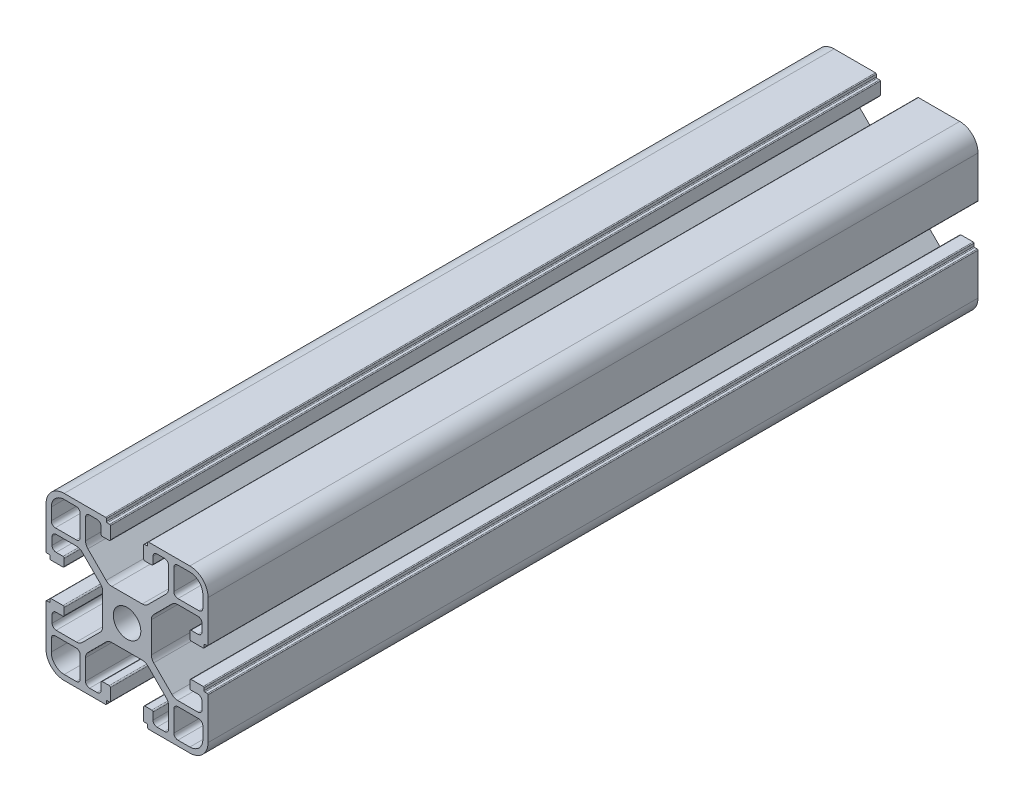
SolidWorks part; units mm, degrees
material "6063-T5"
ref_plane "Front Plane" through (0, 0, 0) normal (0, 0, 1) x (1, 0, 0)
ref_plane "Top Plane" through (0, 0, 0) normal (0, 1, 0) x (1, 0, 0)
ref_plane "Right Plane" through (0, 0, 0) normal (1, 0, 0) x (0, 0, -1)
sketch "Sketch2" plane through (0, 0, 0) normal (0, 0, 1) x (1, 0, 0)
  line L0 (4.5, 0) -> (14.7, 0)
  line L1 (40, 4.5) -> (40, 14.7)
  line L2 (35.5, 40) -> (25.3, 40)
  line L3 (0, 35.5) -> (0, 25.3)
  line L4 (15.9, 1.2) -> (15.9, 4.2)
  line L5 (24.1, 1.2) -> (24.1, 4.2)
  line L6 (38.8, 24.1) -> (35.8, 24.1)
  line L7 (35.5, 24.4) -> (35.5, 26.1)
  line L8 (14, 23.7574) -> (14, 16.2426)
  line L9 (16.2426, 14) -> (23.7574, 14)
  line L10 (26, 16.2426) -> (26, 23.7574)
  line L11 (13.4142, 14.8284) -> (8.9216, 10.3358)
  line L12 (23.7574, 26) -> (16.2426, 26)
  line L13 (4.5, 24.4) -> (4.5, 26.1)
  line L14 (1.2, 24.1) -> (4.2, 24.1)
  line L15 (15.9, 38.8) -> (15.9, 35.8)
  line L16 (14.8284, 26.5858) -> (10.3358, 31.0784)
  line L17 (13.4142, 25.1716) -> (8.9216, 29.6642)
  line L18 (14.8284, 13.4142) -> (10.3358, 8.9216)
  line L19 (25.1716, 13.4142) -> (29.6642, 8.9216)
  line L20 (26.5858, 14.8284) -> (31.0784, 10.3358)
  line L21 (26.5858, 25.1716) -> (31.0784, 29.6642)
  line L22 (25.1716, 26.5858) -> (29.6642, 31.0784)
  line L23 (24.1, 38.8) -> (24.1, 35.8)
  line L24 (14.7, 40) -> (4.5, 40)
  line L25 (25.3, 0) -> (35.5, 0)
  line L26 (38.8, 15.9) -> (35.8, 15.9)
  line L27 (40, 25.3) -> (40, 35.5)
  line L28 (1.2, 15.9) -> (4.2, 15.9)
  line L29 (0, 14.7) -> (0, 4.5)
  line L30 (4.5, 15.6) -> (4.5, 13.9)
  line L31 (35.5, 15.6) -> (35.5, 13.9)
  line L32 (15.6, 35.5) -> (13.9, 35.5)
  line L33 (24.4, 35.5) -> (26.1, 35.5)
  line L34 (15.6, 4.5) -> (13.9, 4.5)
  line L35 (24.4, 4.5) -> (26.1, 4.5)
  line L36 (12.6, 38.5) -> (10.75, 38.5)
  line L37 (1.5, 12.6) -> (1.5, 10.75)
  line L38 (27.4, 1.5) -> (29.25, 1.5)
  line L39 (38.5, 27.4) -> (38.5, 29.25)
  line L40 (38.5, 10.75) -> (38.5, 12.6)
  line L41 (29.25, 38.5) -> (27.4, 38.5)
  line L42 (1.5, 29.25) -> (1.5, 27.4)
  line L43 (10.75, 1.5) -> (12.6, 1.5)
  line L44 (35.8, 26.4) -> (37.5, 26.4)
  line L45 (35.8, 13.6) -> (37.5, 13.6)
  line L46 (4.2, 26.4) -> (2.5, 26.4)
  line L47 (13.6, 35.8) -> (13.6, 37.5)
  line L48 (26.4, 35.8) -> (26.4, 37.5)
  line L49 (4.2, 13.6) -> (2.5, 13.6)
  line L50 (13.6, 4.2) -> (13.6, 2.5)
  line L51 (26.4, 4.2) -> (26.4, 2.5)
  line L52 (9.75, 7.5074) -> (9.75, 2.5)
  line L53 (30.25, 7.5074) -> (30.25, 2.5)
  line L54 (9.75, 37.5) -> (9.75, 32.4926)
  line L55 (30.25, 37.5) -> (30.25, 32.4926)
  line L56 (32.4926, 30.25) -> (37.5, 30.25)
  line L57 (37.5, 9.75) -> (32.4926, 9.75)
  line L58 (2.5, 30.25) -> (7.5074, 30.25)
  line L59 (2.5, 9.75) -> (7.5074, 9.75)
  line L60 (31.55, 37.7) -> (31.55, 32.55)
  line L61 (32.55, 31.55) -> (37.7, 31.55)
  line L62 (1.3, 35.5) -> (1.3, 32.55)
  line L63 (4.5, 38.7) -> (7.45, 38.7)
  line L64 (32.55, 38.7) -> (35.5, 38.7)
  line L65 (38.7, 35.5) -> (38.7, 32.55)
  line L66 (8.45, 37.7) -> (8.45, 32.55)
  line L67 (2.3, 31.55) -> (7.45, 31.55)
  line L68 (1.3, 7.45) -> (1.3, 4.5)
  line L69 (2.3, 8.45) -> (7.45, 8.45)
  line L70 (8.45, 7.45) -> (8.45, 2.3)
  line L71 (4.5, 1.3) -> (7.45, 1.3)
  line L72 (31.55, 7.45) -> (31.55, 2.3)
  line L73 (32.55, 8.45) -> (37.7, 8.45)
  line L74 (38.7, 7.45) -> (38.7, 4.5)
  line L75 (32.55, 1.3) -> (35.5, 1.3)
  line L77 (14.9, 39.8) -> (14.9, 39.2)
  line L78 (15.1, 39) -> (15.7, 39)
  line L79 (25.1, 39.8) -> (25.1, 39.2)
  line L80 (24.9, 39) -> (24.3, 39)
  line L81 (25.1, 0.2) -> (25.1, 0.8)
  line L82 (24.9, 1) -> (24.3, 1)
  line L83 (14.9, 0.2) -> (14.9, 0.8)
  line L84 (15.1, 1) -> (15.7, 1)
  line L85 (0.2, 25.1) -> (0.8, 25.1)
  line L86 (1, 24.9) -> (1, 24.3)
  line L87 (0.2, 14.9) -> (0.8, 14.9)
  line L88 (1, 15.1) -> (1, 15.7)
  line L89 (39.8, 25.1) -> (39.2, 25.1)
  line L90 (39, 24.9) -> (39, 24.3)
  line L91 (39, 15.7) -> (39, 15.1)
  line L92 (39.2, 14.9) -> (39.8, 14.9)
  circle A0 centre (20, 20) radius 3.4
  arc A1 (1.3, 35.5) -> (4.5, 38.7) centre (4.5, 35.5) cw
  arc A2 (1.3, 4.5) -> (4.5, 1.3) centre (4.5, 4.5) ccw
  arc A3 (38.7, 4.5) -> (35.5, 1.3) centre (35.5, 4.5) cw
  arc A4 (35.5, 38.7) -> (38.7, 35.5) centre (35.5, 35.5) cw
  arc A5 (40, 35.5) -> (35.5, 40) centre (35.5, 35.5) ccw
  arc A6 (35.5, 0) -> (40, 4.5) centre (35.5, 4.5) ccw
  arc A7 (4.5, 0) -> (0, 4.5) centre (4.5, 4.5) cw
  arc A8 (4.5, 40) -> (0, 35.5) centre (4.5, 35.5) ccw
  arc A9 (13.4142, 14.8284) -> (14, 16.2426) centre (12, 16.2426) ccw
  arc A10 (7.5074, 9.75) -> (8.9216, 10.3358) centre (7.5074, 11.75) ccw
  arc A11 (9.75, 7.5074) -> (10.3358, 8.9216) centre (11.75, 7.5074) cw
  arc A12 (30.25, 7.5074) -> (29.6642, 8.9216) centre (28.25, 7.5074) ccw
  arc A13 (14.8284, 13.4142) -> (16.2426, 14) centre (16.2426, 12) cw
  arc A14 (25.1716, 13.4142) -> (23.7574, 14) centre (23.7574, 12) ccw
  arc A15 (32.4926, 9.75) -> (31.0784, 10.3358) centre (32.4926, 11.75) cw
  arc A16 (26.5858, 14.8284) -> (26, 16.2426) centre (28, 16.2426) cw
  arc A17 (32.4926, 30.25) -> (31.0784, 29.6642) centre (32.4926, 28.25) ccw
  arc A18 (26.5858, 25.1716) -> (26, 23.7574) centre (28, 23.7574) ccw
  arc A19 (13.4142, 25.1716) -> (14, 23.7574) centre (12, 23.7574) cw
  arc A20 (7.5074, 30.25) -> (8.9216, 29.6642) centre (7.5074, 28.25) cw
  arc A21 (9.75, 32.4926) -> (10.3358, 31.0784) centre (11.75, 32.4926) ccw
  arc A22 (30.25, 32.4926) -> (29.6642, 31.0784) centre (28.25, 32.4926) cw
  arc A23 (25.1716, 26.5858) -> (23.7574, 26) centre (23.7574, 28) cw
  arc A24 (14.8284, 26.5858) -> (16.2426, 26) centre (16.2426, 28) ccw
  arc A25 (37.7, 8.45) -> (38.7, 7.45) centre (37.7, 7.45) cw
  arc A26 (31.55, 2.3) -> (32.55, 1.3) centre (32.55, 2.3) ccw
  arc A27 (31.55, 7.45) -> (32.55, 8.45) centre (32.55, 7.45) cw
  arc A28 (8.45, 2.3) -> (7.45, 1.3) centre (7.45, 2.3) cw
  arc A29 (1.3, 7.45) -> (2.3, 8.45) centre (2.3, 7.45) cw
  arc A30 (7.45, 8.45) -> (8.45, 7.45) centre (7.45, 7.45) cw
  arc A31 (38.7, 32.55) -> (37.7, 31.55) centre (37.7, 32.55) cw
  arc A32 (31.55, 32.55) -> (32.55, 31.55) centre (32.55, 32.55) ccw
  arc A33 (31.55, 37.7) -> (32.55, 38.7) centre (32.55, 37.7) cw
  arc A34 (7.45, 38.7) -> (8.45, 37.7) centre (7.45, 37.7) cw
  arc A35 (8.45, 32.55) -> (7.45, 31.55) centre (7.45, 32.55) cw
  arc A36 (1.3, 32.55) -> (2.3, 31.55) centre (2.3, 32.55) ccw
  arc A37 (30.25, 2.5) -> (29.25, 1.5) centre (29.25, 2.5) cw
  arc A38 (26.4, 2.5) -> (27.4, 1.5) centre (27.4, 2.5) ccw
  arc A39 (13.6, 2.5) -> (12.6, 1.5) centre (12.6, 2.5) cw
  arc A40 (9.75, 2.5) -> (10.75, 1.5) centre (10.75, 2.5) ccw
  arc A41 (26.4, 37.5) -> (27.4, 38.5) centre (27.4, 37.5) cw
  arc A42 (30.25, 37.5) -> (29.25, 38.5) centre (29.25, 37.5) ccw
  arc A43 (37.5, 26.4) -> (38.5, 27.4) centre (37.5, 27.4) ccw
  arc A44 (37.5, 30.25) -> (38.5, 29.25) centre (37.5, 29.25) cw
  arc A45 (37.5, 13.6) -> (38.5, 12.6) centre (37.5, 12.6) cw
  arc A46 (37.5, 9.75) -> (38.5, 10.75) centre (37.5, 10.75) ccw
  arc A47 (2.5, 9.75) -> (1.5, 10.75) centre (2.5, 10.75) cw
  arc A48 (2.5, 13.6) -> (1.5, 12.6) centre (2.5, 12.6) ccw
  arc A49 (2.5, 26.4) -> (1.5, 27.4) centre (2.5, 27.4) cw
  arc A50 (2.5, 30.25) -> (1.5, 29.25) centre (2.5, 29.25) ccw
  arc A51 (9.75, 37.5) -> (10.75, 38.5) centre (10.75, 37.5) cw
  arc A52 (13.6, 37.5) -> (12.6, 38.5) centre (12.6, 37.5) ccw
  arc A53 (26.1, 35.5) -> (26.4, 35.8) centre (26.1, 35.8) ccw
  arc A54 (24.1, 35.8) -> (24.4, 35.5) centre (24.4, 35.8) ccw
  arc A55 (15.9, 35.8) -> (15.6, 35.5) centre (15.6, 35.8) cw
  arc A56 (13.9, 35.5) -> (13.6, 35.8) centre (13.9, 35.8) cw
  arc A57 (13.9, 4.5) -> (13.6, 4.2) centre (13.9, 4.2) ccw
  arc A58 (15.9, 4.2) -> (15.6, 4.5) centre (15.6, 4.2) ccw
  arc A59 (24.1, 4.2) -> (24.4, 4.5) centre (24.4, 4.2) cw
  arc A60 (26.1, 4.5) -> (26.4, 4.2) centre (26.1, 4.2) cw
  arc A61 (35.5, 13.9) -> (35.8, 13.6) centre (35.8, 13.9) ccw
  arc A62 (35.8, 15.9) -> (35.5, 15.6) centre (35.8, 15.6) ccw
  arc A63 (35.8, 24.1) -> (35.5, 24.4) centre (35.8, 24.4) cw
  arc A64 (35.5, 26.1) -> (35.8, 26.4) centre (35.8, 26.1) cw
  arc A65 (4.5, 13.9) -> (4.2, 13.6) centre (4.2, 13.9) cw
  arc A66 (4.2, 15.9) -> (4.5, 15.6) centre (4.2, 15.6) cw
  arc A67 (4.2, 24.1) -> (4.5, 24.4) centre (4.2, 24.4) ccw
  arc A68 (4.5, 26.1) -> (4.2, 26.4) centre (4.2, 26.1) ccw
  arc A69 (25.3, 0) -> (25.1, 0.2) centre (25.3, 0.2) cw
  arc A70 (25.1, 0.8) -> (24.9, 1) centre (24.9, 0.8) ccw
  arc A71 (24.3, 1) -> (24.1, 1.2) centre (24.3, 1.2) cw
  arc A72 (14.7, 0) -> (14.9, 0.2) centre (14.7, 0.2) ccw
  arc A73 (14.9, 0.8) -> (15.1, 1) centre (15.1, 0.8) cw
  arc A74 (15.7, 1) -> (15.9, 1.2) centre (15.7, 1.2) ccw
  arc A75 (39.8, 14.9) -> (40, 14.7) centre (39.8, 14.7) cw
  arc A76 (39, 15.1) -> (39.2, 14.9) centre (39.2, 15.1) ccw
  arc A77 (38.8, 15.9) -> (39, 15.7) centre (38.8, 15.7) cw
  arc A78 (0, 25.3) -> (0.2, 25.1) centre (0.2, 25.3) ccw
  arc A79 (0.8, 25.1) -> (1, 24.9) centre (0.8, 24.9) cw
  arc A80 (1, 24.3) -> (1.2, 24.1) centre (1.2, 24.3) ccw
  arc A81 (0, 14.7) -> (0.2, 14.9) centre (0.2, 14.7) cw
  arc A82 (0.8, 14.9) -> (1, 15.1) centre (0.8, 15.1) ccw
  arc A83 (1, 15.7) -> (1.2, 15.9) centre (1.2, 15.7) cw
  arc A84 (39, 24.3) -> (38.8, 24.1) centre (38.8, 24.3) cw
  arc A85 (39.2, 25.1) -> (39, 24.9) centre (39.2, 24.9) ccw
  arc A86 (40, 25.3) -> (39.8, 25.1) centre (39.8, 25.3) cw
  arc A87 (24.3, 39) -> (24.1, 38.8) centre (24.3, 38.8) ccw
  arc A88 (25.1, 39.2) -> (24.9, 39) centre (24.9, 39.2) cw
  arc A89 (25.3, 40) -> (25.1, 39.8) centre (25.3, 39.8) ccw
  arc A90 (14.9, 39.2) -> (15.1, 39) centre (15.1, 39.2) ccw
  arc A91 (15.7, 39) -> (15.9, 38.8) centre (15.7, 38.8) cw
  arc A92 (14.7, 40) -> (14.9, 39.8) centre (14.7, 39.8) cw
  point P93 (0, 0)
extrude "Boss-Extrude1" add sketch "Sketch2" along normal blind 190
sketch "Sketch3" plane through (0, 0, 190) normal (0, 0, 1) x (1, 0, 0)
  line L76 (25.3, 0) -> (35.5, 0)
  line L77 (40, 4.5) -> (40, 14.7)
  line L78 (39.8, 14.9) -> (39.2, 14.9)
  line L79 (39, 15.1) -> (39, 15.7)
  line L80 (38.8, 15.9) -> (35.8, 15.9)
  line L81 (35.5, 15.6) -> (35.5, 13.9)
  line L82 (35.8, 13.6) -> (37.5, 13.6)
  line L83 (38.5, 12.6) -> (38.5, 10.75)
  line L84 (37.5, 9.75) -> (32.4926, 9.75)
  line L85 (31.0784, 10.3358) -> (26.5858, 14.8284)
  line L86 (26, 16.2426) -> (26, 23.7574)
  line L87 (26.5858, 25.1716) -> (31.0784, 29.6642)
  line L88 (32.4926, 30.25) -> (37.5, 30.25)
  line L89 (38.5, 29.25) -> (38.5, 27.4)
  line L90 (37.5, 26.4) -> (35.8, 26.4)
  line L91 (35.5, 26.1) -> (35.5, 24.4)
  line L92 (35.8, 24.1) -> (38.8, 24.1)
  line L93 (39, 24.3) -> (39, 24.9)
  line L94 (39.2, 25.1) -> (39.8, 25.1)
  line L95 (40, 25.3) -> (40, 35.5)
  line L96 (35.5, 40) -> (25.3, 40)
  line L97 (25.1, 39.8) -> (25.1, 39.2)
  line L98 (24.9, 39) -> (24.3, 39)
  line L99 (24.1, 38.8) -> (24.1, 35.8)
  line L100 (24.4, 35.5) -> (26.1, 35.5)
  line L101 (26.4, 35.8) -> (26.4, 37.5)
  line L102 (27.4, 38.5) -> (29.25, 38.5)
  line L103 (30.25, 37.5) -> (30.25, 32.4926)
  line L104 (29.6642, 31.0784) -> (25.1716, 26.5858)
  line L105 (23.7574, 26) -> (16.2426, 26)
  line L106 (14.8284, 26.5858) -> (10.3358, 31.0784)
  line L107 (9.75, 32.4926) -> (9.75, 37.5)
  line L108 (10.75, 38.5) -> (12.6, 38.5)
  line L109 (13.6, 37.5) -> (13.6, 35.8)
  line L110 (13.9, 35.5) -> (15.6, 35.5)
  line L111 (15.9, 35.8) -> (15.9, 38.8)
  line L112 (15.7, 39) -> (15.1, 39)
  line L113 (14.9, 39.2) -> (14.9, 39.8)
  line L114 (14.7, 40) -> (4.5, 40)
  line L115 (0, 35.5) -> (0, 25.3)
  line L116 (0.2, 25.1) -> (0.8, 25.1)
  line L117 (1, 24.9) -> (1, 24.3)
  line L118 (1.2, 24.1) -> (4.2, 24.1)
  line L119 (4.5, 24.4) -> (4.5, 26.1)
  line L120 (4.2, 26.4) -> (2.5, 26.4)
  line L121 (1.5, 27.4) -> (1.5, 29.25)
  line L122 (2.5, 30.25) -> (7.5074, 30.25)
  line L123 (8.9216, 29.6642) -> (13.4142, 25.1716)
  line L124 (14, 23.7574) -> (14, 16.2426)
  line L125 (13.4142, 14.8284) -> (8.9216, 10.3358)
  line L126 (7.5074, 9.75) -> (2.5, 9.75)
  line L127 (1.5, 10.75) -> (1.5, 12.6)
  line L128 (2.5, 13.6) -> (4.2, 13.6)
  line L129 (4.5, 13.9) -> (4.5, 15.6)
  line L130 (4.2, 15.9) -> (1.2, 15.9)
  line L131 (1, 15.7) -> (1, 15.1)
  line L132 (0.8, 14.9) -> (0.2, 14.9)
  line L133 (0, 14.7) -> (0, 4.5)
  line L134 (4.5, 0) -> (14.7, 0)
  line L135 (14.9, 0.2) -> (14.9, 0.8)
  line L136 (15.1, 1) -> (15.7, 1)
  line L137 (15.9, 1.2) -> (15.9, 4.2)
  line L138 (15.6, 4.5) -> (13.9, 4.5)
  line L139 (13.6, 4.2) -> (13.6, 2.5)
  line L140 (12.6, 1.5) -> (10.75, 1.5)
  line L141 (9.75, 2.5) -> (9.75, 7.5074)
  line L142 (10.3358, 8.9216) -> (14.8284, 13.4142)
  line L143 (16.2426, 14) -> (23.7574, 14)
  line L144 (25.1716, 13.4142) -> (29.6642, 8.9216)
  line L145 (30.25, 7.5074) -> (30.25, 2.5)
  line L146 (29.25, 1.5) -> (27.4, 1.5)
  line L147 (26.4, 2.5) -> (26.4, 4.2)
  line L148 (26.1, 4.5) -> (24.4, 4.5)
  line L149 (24.1, 4.2) -> (24.1, 1.2)
  line L150 (24.3, 1) -> (24.9, 1)
  line L151 (25.1, 0.8) -> (25.1, 0.2)
  line L152 (25.3, 0) -> (35.5, 0)
  line L153 (40, 4.5) -> (40, 14.7)
  line L154 (39.8, 14.9) -> (39.2, 14.9)
  line L155 (39, 15.1) -> (39, 15.7)
  line L156 (38.8, 15.9) -> (35.8, 15.9)
  line L157 (35.5, 15.6) -> (35.5, 13.9)
  line L158 (35.8, 13.6) -> (37.5, 13.6)
  line L159 (38.5, 12.6) -> (38.5, 10.75)
  line L160 (37.5, 9.75) -> (32.4926, 9.75)
  line L161 (31.0784, 10.3358) -> (26.5858, 14.8284)
  line L162 (26, 16.2426) -> (26, 23.7574)
  line L163 (26.5858, 25.1716) -> (31.0784, 29.6642)
  line L164 (32.4926, 30.25) -> (37.5, 30.25)
  line L165 (38.5, 29.25) -> (38.5, 27.4)
  line L166 (37.5, 26.4) -> (35.8, 26.4)
  line L167 (35.5, 26.1) -> (35.5, 24.4)
  line L168 (35.8, 24.1) -> (38.8, 24.1)
  line L169 (39, 24.3) -> (39, 24.9)
  line L170 (39.2, 25.1) -> (39.8, 25.1)
  line L171 (40, 25.3) -> (40, 35.5)
  line L172 (35.5, 40) -> (25.3, 40)
  line L173 (25.1, 39.8) -> (25.1, 39.2)
  line L174 (24.9, 39) -> (24.3, 39)
  line L175 (24.1, 38.8) -> (24.1, 35.8)
  line L176 (24.4, 35.5) -> (26.1, 35.5)
  line L177 (26.4, 35.8) -> (26.4, 37.5)
  line L178 (27.4, 38.5) -> (29.25, 38.5)
  line L179 (30.25, 37.5) -> (30.25, 32.4926)
  line L180 (29.6642, 31.0784) -> (25.1716, 26.5858)
  line L181 (23.7574, 26) -> (16.2426, 26)
  line L182 (14.8284, 26.5858) -> (10.3358, 31.0784)
  line L183 (9.75, 32.4926) -> (9.75, 37.5)
  line L184 (10.75, 38.5) -> (12.6, 38.5)
  line L185 (13.6, 37.5) -> (13.6, 35.8)
  line L186 (13.9, 35.5) -> (15.6, 35.5)
  line L187 (15.9, 35.8) -> (15.9, 38.8)
  line L188 (15.7, 39) -> (15.1, 39)
  line L189 (14.9, 39.2) -> (14.9, 39.8)
  line L190 (14.7, 40) -> (4.5, 40)
  line L191 (0, 35.5) -> (0, 25.3)
  line L192 (0.2, 25.1) -> (0.8, 25.1)
  line L193 (1, 24.9) -> (1, 24.3)
  line L194 (1.2, 24.1) -> (4.2, 24.1)
  line L195 (4.5, 24.4) -> (4.5, 26.1)
  line L196 (4.2, 26.4) -> (2.5, 26.4)
  line L197 (1.5, 27.4) -> (1.5, 29.25)
  line L198 (2.5, 30.25) -> (7.5074, 30.25)
  line L199 (8.9216, 29.6642) -> (13.4142, 25.1716)
  line L200 (14, 23.7574) -> (14, 16.2426)
  line L201 (13.4142, 14.8284) -> (8.9216, 10.3358)
  line L202 (7.5074, 9.75) -> (2.5, 9.75)
  line L203 (1.5, 10.75) -> (1.5, 12.6)
  line L204 (2.5, 13.6) -> (4.2, 13.6)
  line L205 (4.5, 13.9) -> (4.5, 15.6)
  line L206 (4.2, 15.9) -> (1.2, 15.9)
  line L207 (1, 15.7) -> (1, 15.1)
  line L208 (0.8, 14.9) -> (0.2, 14.9)
  line L209 (0, 14.7) -> (0, 4.5)
  line L210 (4.5, 0) -> (14.7, 0)
  line L211 (14.9, 0.2) -> (14.9, 0.8)
  line L212 (15.1, 1) -> (15.7, 1)
  line L213 (15.9, 1.2) -> (15.9, 4.2)
  line L214 (15.6, 4.5) -> (13.9, 4.5)
  line L215 (13.6, 4.2) -> (13.6, 2.5)
  line L216 (12.6, 1.5) -> (10.75, 1.5)
  line L217 (9.75, 2.5) -> (9.75, 7.5074)
  line L218 (10.3358, 8.9216) -> (14.8284, 13.4142)
  line L219 (16.2426, 14) -> (23.7574, 14)
  line L220 (25.1716, 13.4142) -> (29.6642, 8.9216)
  line L221 (30.25, 7.5074) -> (30.25, 2.5)
  line L222 (29.25, 1.5) -> (27.4, 1.5)
  line L223 (26.4, 2.5) -> (26.4, 4.2)
  line L224 (26.1, 4.5) -> (24.4, 4.5)
  line L225 (24.1, 4.2) -> (24.1, 1.2)
  line L226 (24.3, 1) -> (24.9, 1)
  line L227 (25.1, 0.8) -> (25.1, 0.2)
  arc A76 (25.1, 0.2) -> (25.3, 0) centre (25.3, 0.2) ccw
  arc A77 (35.5, 0) -> (40, 4.5) centre (35.5, 4.5) ccw
  arc A78 (40, 14.7) -> (39.8, 14.9) centre (39.8, 14.7) ccw
  arc A79 (39, 15.1) -> (39.2, 14.9) centre (39.2, 15.1) ccw
  arc A80 (39, 15.7) -> (38.8, 15.9) centre (38.8, 15.7) ccw
  arc A81 (35.8, 15.9) -> (35.5, 15.6) centre (35.8, 15.6) ccw
  arc A82 (35.5, 13.9) -> (35.8, 13.6) centre (35.8, 13.9) ccw
  arc A83 (38.5, 12.6) -> (37.5, 13.6) centre (37.5, 12.6) ccw
  arc A84 (37.5, 9.75) -> (38.5, 10.75) centre (37.5, 10.75) ccw
  arc A85 (31.0784, 10.3358) -> (32.4926, 9.75) centre (32.4926, 11.75) ccw
  arc A86 (26, 16.2426) -> (26.5858, 14.8284) centre (28, 16.2426) ccw
  arc A87 (26.5858, 25.1716) -> (26, 23.7574) centre (28, 23.7574) ccw
  arc A88 (32.4926, 30.25) -> (31.0784, 29.6642) centre (32.4926, 28.25) ccw
  arc A89 (38.5, 29.25) -> (37.5, 30.25) centre (37.5, 29.25) ccw
  arc A90 (37.5, 26.4) -> (38.5, 27.4) centre (37.5, 27.4) ccw
  arc A91 (35.8, 26.4) -> (35.5, 26.1) centre (35.8, 26.1) ccw
  arc A92 (35.5, 24.4) -> (35.8, 24.1) centre (35.8, 24.4) ccw
  arc A93 (38.8, 24.1) -> (39, 24.3) centre (38.8, 24.3) ccw
  arc A94 (39.2, 25.1) -> (39, 24.9) centre (39.2, 24.9) ccw
  arc A95 (39.8, 25.1) -> (40, 25.3) centre (39.8, 25.3) ccw
  arc A96 (40, 35.5) -> (35.5, 40) centre (35.5, 35.5) ccw
  arc A97 (25.3, 40) -> (25.1, 39.8) centre (25.3, 39.8) ccw
  arc A98 (24.9, 39) -> (25.1, 39.2) centre (24.9, 39.2) ccw
  arc A99 (24.3, 39) -> (24.1, 38.8) centre (24.3, 38.8) ccw
  arc A100 (24.1, 35.8) -> (24.4, 35.5) centre (24.4, 35.8) ccw
  arc A101 (26.1, 35.5) -> (26.4, 35.8) centre (26.1, 35.8) ccw
  arc A102 (27.4, 38.5) -> (26.4, 37.5) centre (27.4, 37.5) ccw
  arc A103 (30.25, 37.5) -> (29.25, 38.5) centre (29.25, 37.5) ccw
  arc A104 (29.6642, 31.0784) -> (30.25, 32.4926) centre (28.25, 32.4926) ccw
  arc A105 (23.7574, 26) -> (25.1716, 26.5858) centre (23.7574, 28) ccw
  arc A106 (14.8284, 26.5858) -> (16.2426, 26) centre (16.2426, 28) ccw
  arc A107 (9.75, 32.4926) -> (10.3358, 31.0784) centre (11.75, 32.4926) ccw
  arc A108 (10.75, 38.5) -> (9.75, 37.5) centre (10.75, 37.5) ccw
  arc A109 (13.6, 37.5) -> (12.6, 38.5) centre (12.6, 37.5) ccw
  arc A110 (13.6, 35.8) -> (13.9, 35.5) centre (13.9, 35.8) ccw
  arc A111 (15.6, 35.5) -> (15.9, 35.8) centre (15.6, 35.8) ccw
  arc A112 (15.9, 38.8) -> (15.7, 39) centre (15.7, 38.8) ccw
  arc A113 (14.9, 39.2) -> (15.1, 39) centre (15.1, 39.2) ccw
  arc A114 (14.9, 39.8) -> (14.7, 40) centre (14.7, 39.8) ccw
  arc A115 (4.5, 40) -> (0, 35.5) centre (4.5, 35.5) ccw
  arc A116 (0, 25.3) -> (0.2, 25.1) centre (0.2, 25.3) ccw
  arc A117 (1, 24.9) -> (0.8, 25.1) centre (0.8, 24.9) ccw
  arc A118 (1, 24.3) -> (1.2, 24.1) centre (1.2, 24.3) ccw
  arc A119 (4.2, 24.1) -> (4.5, 24.4) centre (4.2, 24.4) ccw
  arc A120 (4.5, 26.1) -> (4.2, 26.4) centre (4.2, 26.1) ccw
  arc A121 (1.5, 27.4) -> (2.5, 26.4) centre (2.5, 27.4) ccw
  arc A122 (2.5, 30.25) -> (1.5, 29.25) centre (2.5, 29.25) ccw
  arc A123 (8.9216, 29.6642) -> (7.5074, 30.25) centre (7.5074, 28.25) ccw
  arc A124 (14, 23.7574) -> (13.4142, 25.1716) centre (12, 23.7574) ccw
  arc A125 (13.4142, 14.8284) -> (14, 16.2426) centre (12, 16.2426) ccw
  arc A126 (7.5074, 9.75) -> (8.9216, 10.3358) centre (7.5074, 11.75) ccw
  arc A127 (1.5, 10.75) -> (2.5, 9.75) centre (2.5, 10.75) ccw
  arc A128 (2.5, 13.6) -> (1.5, 12.6) centre (2.5, 12.6) ccw
  arc A129 (4.2, 13.6) -> (4.5, 13.9) centre (4.2, 13.9) ccw
  arc A130 (4.5, 15.6) -> (4.2, 15.9) centre (4.2, 15.6) ccw
  arc A131 (1.2, 15.9) -> (1, 15.7) centre (1.2, 15.7) ccw
  arc A132 (0.8, 14.9) -> (1, 15.1) centre (0.8, 15.1) ccw
  arc A133 (0.2, 14.9) -> (0, 14.7) centre (0.2, 14.7) ccw
  arc A134 (0, 4.5) -> (4.5, 0) centre (4.5, 4.5) ccw
  arc A135 (14.7, 0) -> (14.9, 0.2) centre (14.7, 0.2) ccw
  arc A136 (15.1, 1) -> (14.9, 0.8) centre (15.1, 0.8) ccw
  arc A137 (15.7, 1) -> (15.9, 1.2) centre (15.7, 1.2) ccw
  arc A138 (15.9, 4.2) -> (15.6, 4.5) centre (15.6, 4.2) ccw
  arc A139 (13.9, 4.5) -> (13.6, 4.2) centre (13.9, 4.2) ccw
  arc A140 (12.6, 1.5) -> (13.6, 2.5) centre (12.6, 2.5) ccw
  arc A141 (9.75, 2.5) -> (10.75, 1.5) centre (10.75, 2.5) ccw
  arc A142 (10.3358, 8.9216) -> (9.75, 7.5074) centre (11.75, 7.5074) ccw
  arc A143 (16.2426, 14) -> (14.8284, 13.4142) centre (16.2426, 12) ccw
  arc A144 (25.1716, 13.4142) -> (23.7574, 14) centre (23.7574, 12) ccw
  arc A145 (30.25, 7.5074) -> (29.6642, 8.9216) centre (28.25, 7.5074) ccw
  arc A146 (29.25, 1.5) -> (30.25, 2.5) centre (29.25, 2.5) ccw
  arc A147 (26.4, 2.5) -> (27.4, 1.5) centre (27.4, 2.5) ccw
  arc A148 (26.4, 4.2) -> (26.1, 4.5) centre (26.1, 4.2) ccw
  arc A149 (24.4, 4.5) -> (24.1, 4.2) centre (24.4, 4.2) ccw
  arc A150 (24.1, 1.2) -> (24.3, 1) centre (24.3, 1.2) ccw
  arc A151 (25.1, 0.8) -> (24.9, 1) centre (24.9, 0.8) ccw
  arc A152 (25.1, 0.2) -> (25.3, 0) centre (25.3, 0.2) ccw
  arc A153 (35.5, 0) -> (40, 4.5) centre (35.5, 4.5) ccw
  arc A154 (40, 14.7) -> (39.8, 14.9) centre (39.8, 14.7) ccw
  arc A155 (39, 15.1) -> (39.2, 14.9) centre (39.2, 15.1) ccw
  arc A156 (39, 15.7) -> (38.8, 15.9) centre (38.8, 15.7) ccw
  arc A157 (35.8, 15.9) -> (35.5, 15.6) centre (35.8, 15.6) ccw
  arc A158 (35.5, 13.9) -> (35.8, 13.6) centre (35.8, 13.9) ccw
  arc A159 (38.5, 12.6) -> (37.5, 13.6) centre (37.5, 12.6) ccw
  arc A160 (37.5, 9.75) -> (38.5, 10.75) centre (37.5, 10.75) ccw
  arc A161 (31.0784, 10.3358) -> (32.4926, 9.75) centre (32.4926, 11.75) ccw
  arc A162 (26, 16.2426) -> (26.5858, 14.8284) centre (28, 16.2426) ccw
  arc A163 (26.5858, 25.1716) -> (26, 23.7574) centre (28, 23.7574) ccw
  arc A164 (32.4926, 30.25) -> (31.0784, 29.6642) centre (32.4926, 28.25) ccw
  arc A165 (38.5, 29.25) -> (37.5, 30.25) centre (37.5, 29.25) ccw
  arc A166 (37.5, 26.4) -> (38.5, 27.4) centre (37.5, 27.4) ccw
  arc A167 (35.8, 26.4) -> (35.5, 26.1) centre (35.8, 26.1) ccw
  arc A168 (35.5, 24.4) -> (35.8, 24.1) centre (35.8, 24.4) ccw
  arc A169 (38.8, 24.1) -> (39, 24.3) centre (38.8, 24.3) ccw
  arc A170 (39.2, 25.1) -> (39, 24.9) centre (39.2, 24.9) ccw
  arc A171 (39.8, 25.1) -> (40, 25.3) centre (39.8, 25.3) ccw
  arc A172 (40, 35.5) -> (35.5, 40) centre (35.5, 35.5) ccw
  arc A173 (25.3, 40) -> (25.1, 39.8) centre (25.3, 39.8) ccw
  arc A174 (24.9, 39) -> (25.1, 39.2) centre (24.9, 39.2) ccw
  arc A175 (24.3, 39) -> (24.1, 38.8) centre (24.3, 38.8) ccw
  arc A176 (24.1, 35.8) -> (24.4, 35.5) centre (24.4, 35.8) ccw
  arc A177 (26.1, 35.5) -> (26.4, 35.8) centre (26.1, 35.8) ccw
  arc A178 (27.4, 38.5) -> (26.4, 37.5) centre (27.4, 37.5) ccw
  arc A179 (30.25, 37.5) -> (29.25, 38.5) centre (29.25, 37.5) ccw
  arc A180 (29.6642, 31.0784) -> (30.25, 32.4926) centre (28.25, 32.4926) ccw
  arc A181 (23.7574, 26) -> (25.1716, 26.5858) centre (23.7574, 28) ccw
  arc A182 (14.8284, 26.5858) -> (16.2426, 26) centre (16.2426, 28) ccw
  arc A183 (9.75, 32.4926) -> (10.3358, 31.0784) centre (11.75, 32.4926) ccw
  arc A184 (10.75, 38.5) -> (9.75, 37.5) centre (10.75, 37.5) ccw
  arc A185 (13.6, 37.5) -> (12.6, 38.5) centre (12.6, 37.5) ccw
  arc A186 (13.6, 35.8) -> (13.9, 35.5) centre (13.9, 35.8) ccw
  arc A187 (15.6, 35.5) -> (15.9, 35.8) centre (15.6, 35.8) ccw
  arc A188 (15.9, 38.8) -> (15.7, 39) centre (15.7, 38.8) ccw
  arc A189 (14.9, 39.2) -> (15.1, 39) centre (15.1, 39.2) ccw
  arc A190 (14.9, 39.8) -> (14.7, 40) centre (14.7, 39.8) ccw
  arc A191 (4.5, 40) -> (0, 35.5) centre (4.5, 35.5) ccw
  arc A192 (0, 25.3) -> (0.2, 25.1) centre (0.2, 25.3) ccw
  arc A193 (1, 24.9) -> (0.8, 25.1) centre (0.8, 24.9) ccw
  arc A194 (1, 24.3) -> (1.2, 24.1) centre (1.2, 24.3) ccw
  arc A195 (4.2, 24.1) -> (4.5, 24.4) centre (4.2, 24.4) ccw
  arc A196 (4.5, 26.1) -> (4.2, 26.4) centre (4.2, 26.1) ccw
  arc A197 (1.5, 27.4) -> (2.5, 26.4) centre (2.5, 27.4) ccw
  arc A198 (2.5, 30.25) -> (1.5, 29.25) centre (2.5, 29.25) ccw
  arc A199 (8.9216, 29.6642) -> (7.5074, 30.25) centre (7.5074, 28.25) ccw
  arc A200 (14, 23.7574) -> (13.4142, 25.1716) centre (12, 23.7574) ccw
  arc A201 (13.4142, 14.8284) -> (14, 16.2426) centre (12, 16.2426) ccw
  arc A202 (7.5074, 9.75) -> (8.9216, 10.3358) centre (7.5074, 11.75) ccw
  arc A203 (1.5, 10.75) -> (2.5, 9.75) centre (2.5, 10.75) ccw
  arc A204 (2.5, 13.6) -> (1.5, 12.6) centre (2.5, 12.6) ccw
  arc A205 (4.2, 13.6) -> (4.5, 13.9) centre (4.2, 13.9) ccw
  arc A206 (4.5, 15.6) -> (4.2, 15.9) centre (4.2, 15.6) ccw
  arc A207 (1.2, 15.9) -> (1, 15.7) centre (1.2, 15.7) ccw
  arc A208 (0.8, 14.9) -> (1, 15.1) centre (0.8, 15.1) ccw
  arc A209 (0.2, 14.9) -> (0, 14.7) centre (0.2, 14.7) ccw
  arc A210 (0, 4.5) -> (4.5, 0) centre (4.5, 4.5) ccw
  arc A211 (14.7, 0) -> (14.9, 0.2) centre (14.7, 0.2) ccw
  arc A212 (15.1, 1) -> (14.9, 0.8) centre (15.1, 0.8) ccw
  arc A213 (15.7, 1) -> (15.9, 1.2) centre (15.7, 1.2) ccw
  arc A214 (15.9, 4.2) -> (15.6, 4.5) centre (15.6, 4.2) ccw
  arc A215 (13.9, 4.5) -> (13.6, 4.2) centre (13.9, 4.2) ccw
  arc A216 (12.6, 1.5) -> (13.6, 2.5) centre (12.6, 2.5) ccw
  arc A217 (9.75, 2.5) -> (10.75, 1.5) centre (10.75, 2.5) ccw
  arc A218 (10.3358, 8.9216) -> (9.75, 7.5074) centre (11.75, 7.5074) ccw
  arc A219 (16.2426, 14) -> (14.8284, 13.4142) centre (16.2426, 12) ccw
  arc A220 (25.1716, 13.4142) -> (23.7574, 14) centre (23.7574, 12) ccw
  arc A221 (30.25, 7.5074) -> (29.6642, 8.9216) centre (28.25, 7.5074) ccw
  arc A222 (29.25, 1.5) -> (30.25, 2.5) centre (29.25, 2.5) ccw
  arc A223 (26.4, 2.5) -> (27.4, 1.5) centre (27.4, 2.5) ccw
  arc A224 (26.4, 4.2) -> (26.1, 4.5) centre (26.1, 4.2) ccw
  arc A225 (24.4, 4.5) -> (24.1, 4.2) centre (24.4, 4.2) ccw
  arc A226 (24.1, 1.2) -> (24.3, 1) centre (24.3, 1.2) ccw
  arc A227 (25.1, 0.8) -> (24.9, 1) centre (24.9, 0.8) ccw
  dimension "D1" = 0
sketch "Sketch4" plane through (0, 0, 0) normal (-1, 0, 0) x (0, 0, 1)
  line L0 (15, 20) -> (68, 20) construction
  line L2 (0, 23.7574) -> (0, 16.2426) construction
  circle A0 centre (15, 20) radius 2.5
  circle A1 centre (68, 20) radius 2.5
  dimension "D1" = 5
  dimension "D2" = 53
  dimension "D3" = 15
extrude "Cut-Extrude1" cut sketch "Sketch4" against normal through all
